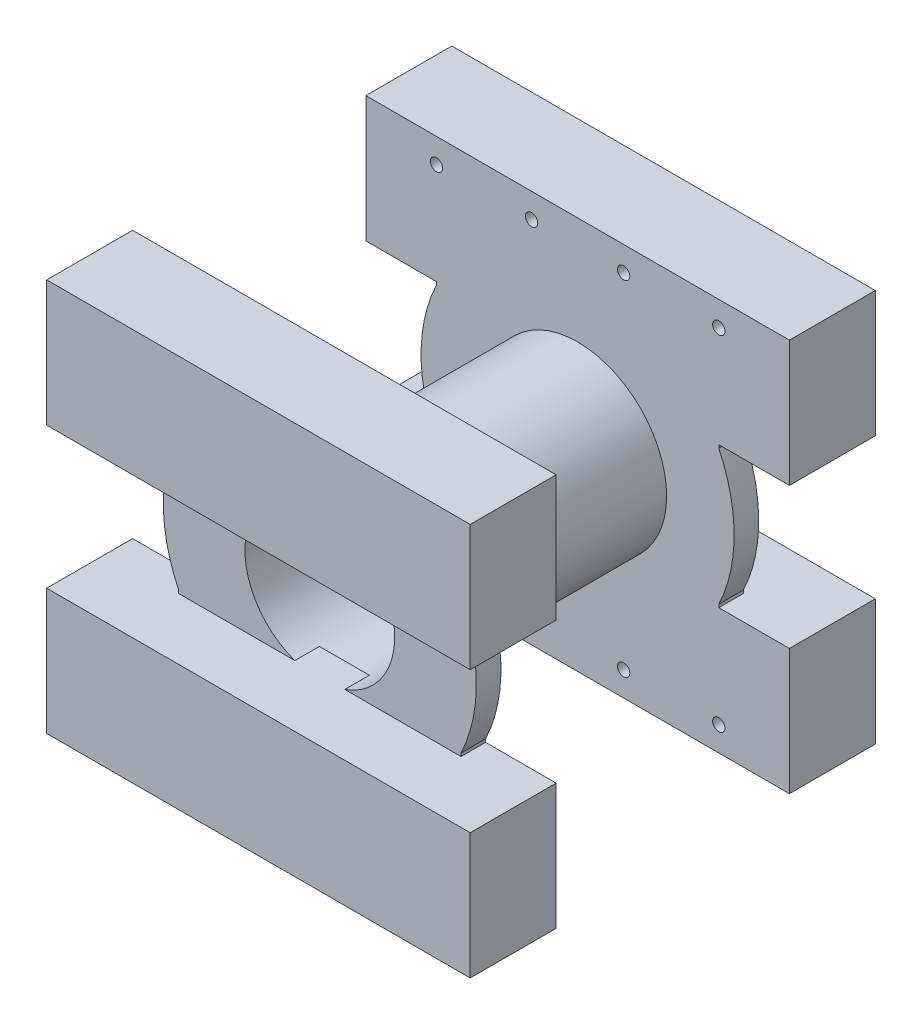
SolidWorks part; units mm, degrees
ref_plane "Front Plane" through (0, 0, 0) normal (0, 0, 1) x (1, 0, 0)
ref_plane "Top Plane" through (0, 0, 0) normal (0, 1, 0) x (1, 0, 0)
ref_plane "Right Plane" through (0, 0, 0) normal (1, 0, 0) x (0, 0, -1)
sketch "Sketch1" plane through (0, 0, 0) normal (0, 0, 1) x (1, 0, 0)
  line L0 (11.5, 5.5057) -> (11.5, 16)
  line L1 (11.5, -16) -> (-11.5, -16)
  line L2 (11.5, -16) -> (11.5, -5.5057)
  line L3 (11.5, 16) -> (-11.5, 16)
  line L4 (-11.5, -16) -> (-11.5, -5.5057)
  line L5 (11.5, -16) -> (-11.5, 16) construction
  line L6 (11.5, 16) -> (-11.5, -16) construction
  line L7 (-11.5, 5.5057) -> (-11.5, 16)
  circle A0 centre (0, 0) radius 6.1
  arc A1 (-11.5, 5.5057) -> (-11.5, -5.5057) centre (0, 0) ccw
  arc A2 (11.5, -5.5057) -> (11.5, 5.5057) centre (0, 0) ccw
  circle A3 centre (0, 0) radius 7.25
  dimension "D1" = 12.2
  dimension "D2" = 25.5
  dimension "D5" = 14.5
  dimension "D3" = 23
  dimension "D4" = 32
extrude "Boss-Extrude1" add sketch "Sketch1" along normal mid plane 2 contours L2 A2 L0 L3 L7 A1 L4 L1 A3 | A3 A0
sketch "Sketch2" plane through (0, 0, 1) normal (0, 0, 1) x (1, 0, 0)
  circle A1 centre (0, 0) radius 6.1
  circle A2 centre (0, 0) radius 7.25
  dimension "D1" = 12.2
  dimension "D2" = 14.5
sketch "Sketch3" plane through (0, 0, -1) normal (0, 0, -1) x (-1, 0, 0)
  line L3 (17.25, 5.75) -> (-17.25, 5.75)
  line L5 (-15.6987, 0) -> (19.4146, 0) construction
  line L6 (17.25, -16) -> (17.25, -5.75)
  line L7 (-17.25, 5.75) -> (-17.25, 16)
  line L8 (-17.25, 16) -> (17.25, 16)
  line L9 (17.25, 16) -> (17.25, 5.75)
  line L10 (-17.25, -16) -> (17.25, -16)
  line L11 (-17.25, -5.75) -> (-17.25, -16)
  line L12 (17.25, -5.75) -> (-17.25, -5.75)
  point P0 (0, 0)
  point P7 (0, 5.75)
  dimension "D1" = 11.5
  dimension "D2" = 34.5
extrude "Boss-Extrude4" add sketch "Sketch2" along normal blind 19
extrude "Boss-Extrude5" add sketch "Sketch3" along normal blind 5 and the other way up to surface
ref_plane "Plane1" through (0, 0, 10.5) normal (0, 0, 1) x (1, 0, 0)
mirror "Mirror1" about plane through (0, 0, 10.5) normal (0, 0, 1) of "Boss-Extrude5", "Boss-Extrude1"
sketch "Sketch4" plane through (0, 0, -6) normal (0, 0, -1) x (-1, 0, 0)
  line L0 (-17.6861, 0) -> (22.8967, 0) construction
  line L1 (-16.2832, 14) -> (14.9805, 14) construction
  line L2 (0, 20.0666) -> (0, -21.7538) construction
  line L3 (-17.25, 16) -> (-17.25, 5.75) construction
  circle A0 centre (-11.5, 14) radius 0.5
  circle A1 centre (-3.75, 14) radius 0.5
  circle A2 centre (3.75, 14) radius 0.5
  circle A3 centre (11.5, 14) radius 0.5
  circle A4 centre (3.75, -14) radius 0.5
  circle A5 centre (-3.75, -14) radius 0.5
  circle A6 centre (-11.5, -14) radius 0.5
  circle A7 centre (11.5, -14) radius 0.5
  point P17 (11.5, -14)
  dimension "D4" = 1
  dimension "D5" = 1
  dimension "D1" = 14
  dimension "D2" = 7.75
  dimension "D3" = 5.75
  dimension "D6" = 7.5
extrude "Cut-Extrude1" cut sketch "Sketch4" against normal blind 10
